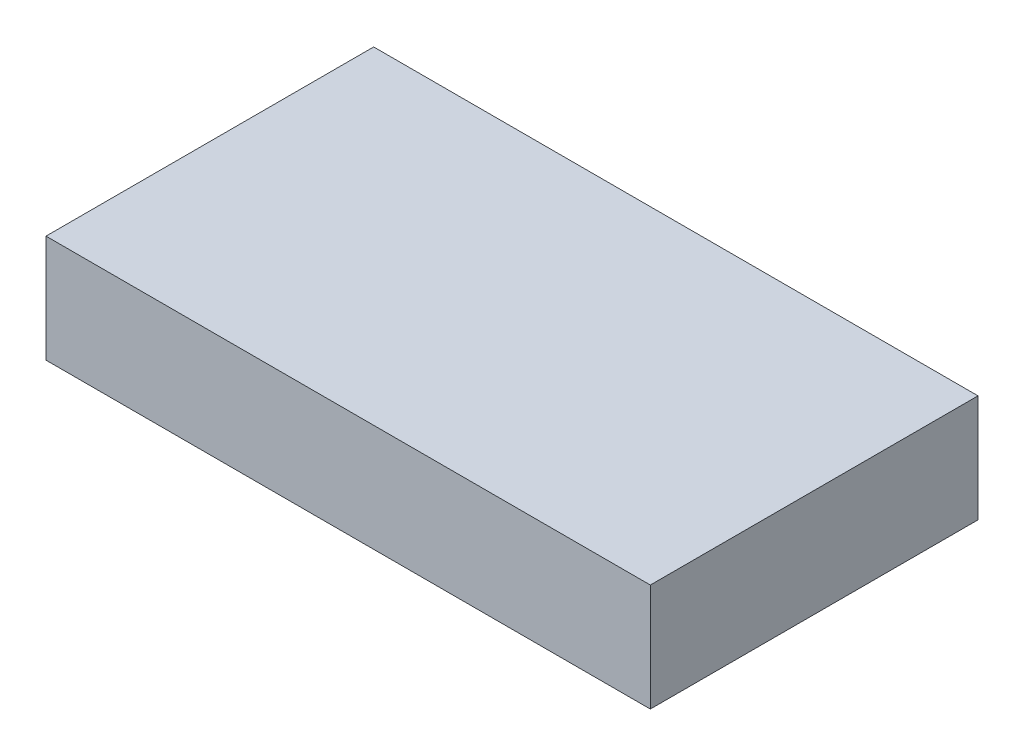
SolidWorks part; units mm, degrees
ref_plane "Front Plane" through (0, 0, 0) normal (0, 0, 1) x (1, 0, 0)
ref_plane "Top Plane" through (0, 0, 0) normal (0, 1, 0) x (1, 0, 0)
ref_plane "Right Plane" through (0, 0, 0) normal (1, 0, 0) x (0, 0, -1)
sketch "Sketch1" plane through (0, 0, 0) normal (0, 1, 0) x (1, 0, 0)
  line L1 (5.625, -3.05) -> (-5.625, -3.05)
  line L2 (5.625, -3.05) -> (5.625, 3.05)
  line L3 (5.625, 3.05) -> (-5.625, 3.05)
  line L4 (-5.625, -3.05) -> (-5.625, 3.05)
  line L5 (5.625, -3.05) -> (-5.625, 3.05) construction
  line L6 (5.625, 3.05) -> (-5.625, -3.05) construction
  point P0 (0, 0)
  dimension "D1" = 11.25
  dimension "D2" = 6.1
extrude "Boss-Extrude1" add sketch "Sketch1" along normal blind 2
sketch "Sketch2" plane through (0, 0, -3.05) normal (0, 0, -1) x (-1, 0, 0)
  line L0 (-5.625, 2) -> (-5.625, 0) construction
  line L1 (5.3075, -1.365) -> (-5.3075, -1.365)
  line L2 (5.3075, -1.365) -> (5.3075, 1.365)
  line L3 (5.3075, 1.365) -> (-5.3075, 1.365)
  line L4 (-5.3075, -1.365) -> (-5.3075, 1.365)
  line L5 (5.3075, -1.365) -> (-5.3075, 1.365) construction
  line L6 (5.3075, 1.365) -> (-5.3075, -1.365) construction
  line L7 (-5.625, 2) -> (5.625, 2) construction
  point P0 (0, 0)
  dimension "D1" = 0.3175
  dimension "D2" = 0.635
extrude "Cut-Extrude1" cut sketch "Sketch2" against normal blind 3.81
sketch "Sketch4" plane through (0, 0, 0.76) normal (0, 0, -1) x (-1, 0, 0)
  line L0 (0, 0) -> (0, 1.365) construction
  line L1 (5.3075, 1.365) -> (-5.3075, 1.365) construction
  line L2 (0, 1.365) -> (0, 0.6825) construction
  line L3 (0, 0.6825) -> (-5.3075, 0.6825) construction
  line L4 (-5.3075, 1.365) -> (-5.3075, 0) construction
  line L5 (-5.3075, 0.6825) -> (5.3075, 0.6825) construction
  line L6 (5.3075, 0) -> (5.3075, 1.365) construction
  line L7 (5.3075, 0.6825) -> (0, 0.6825) construction
  line L8 (1.7691, 0.6825) -> (-1.7691, 0.6825) construction
  line L9 (3.5382, 0.6825) -> (-3.5382, 0.6825) construction
  line L10 (-5.3075, 1.365) -> (-5.3075, 0) construction
  circle A0 centre (-3.5382, 0.6825) radius 0.3091
  circle A1 centre (-1.7691, 0.6825) radius 0.3091
  circle A2 centre (0, 0.6825) radius 0.3091
  circle A3 centre (1.7691, 0.6825) radius 0.3091
  circle A4 centre (3.5382, 0.6825) radius 0.3091
  point P14 (0, 0.6825)
  point P18 (0, 0.6825)
  dimension "D1" = 5.3075
  dimension "D2" = 1.7691
  dimension "D3" = 1.7691
extrude "Boss-Extrude2" add sketch "Sketch4" along normal up to surface (3.81 mm away) up to face at (0, 0.8412, -3.05)
fillet "Fillet1" radius 0.254 5 edges at (-3.2292, 0.6825, -3.05) (-1.4601, 0.6825, -3.05) (0.3091, 0.6825, -3.05) (2.0782, 0.6825, -3.05) (3.8473, 0.6825, -3.05)
